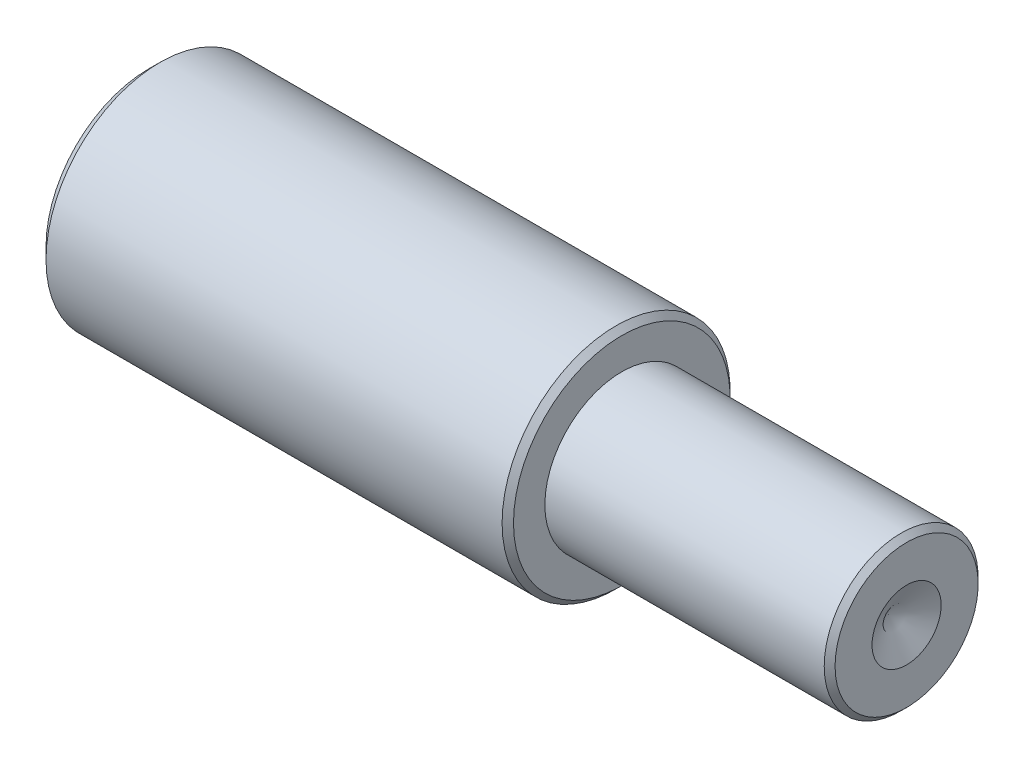
SolidWorks part; units mm, degrees
ref_plane "Спереди" through (0, 0, 0) normal (0, 0, 1) x (1, 0, 0)
ref_plane "Сверху" through (0, 0, 0) normal (0, 1, 0) x (1, 0, 0)
ref_plane "Справа" through (0, 0, 0) normal (1, 0, 0) x (0, 0, -1)
sketch "Эскиз2" plane through (0, 0, 0) normal (0, 1, 0) x (1, 0, 0)
  line L0 (-45.5275, 22.3375) -> (34.4725, 22.3375)
  line L1 (35.4725, 21.3375) -> (35.4725, 15.8375)
  line L2 (35.4725, 15.8375) -> (84.4725, 15.8375)
  line L3 (-47.5275, 20.3375) -> (-47.5275, 2.3375)
  line L4 (85.4245, 14.8855) -> (85.4245, 8.4009)
  line L5 (-47.5275, 2.3375) -> (82.2592, 2.3375)
  line L6 (34.4725, 22.3375) -> (35.4725, 21.3375)
  line L7 (-58.608, 2.3375) -> (159.8552, 2.3375) construction
  line L8 (84.4725, 15.8375) -> (85.4245, 14.8855)
  line L9 (-45.5275, 22.3375) -> (-47.5275, 20.3375)
  line L10 (82.2592, 2.3375) -> (85.4245, 8.4009)
  point P1 (35.4725, 22.3375)
  point P4 (85.4725, 15.8375)
  point P10 (-47.5275, 22.3375)
  dimension "D1" = 20
  dimension "D2" = 13.5
  dimension "D3" = 2
  dimension "D4" = 45
revolve "Повернуть2" add sketch "Эскиз2" angle 360 about L7
